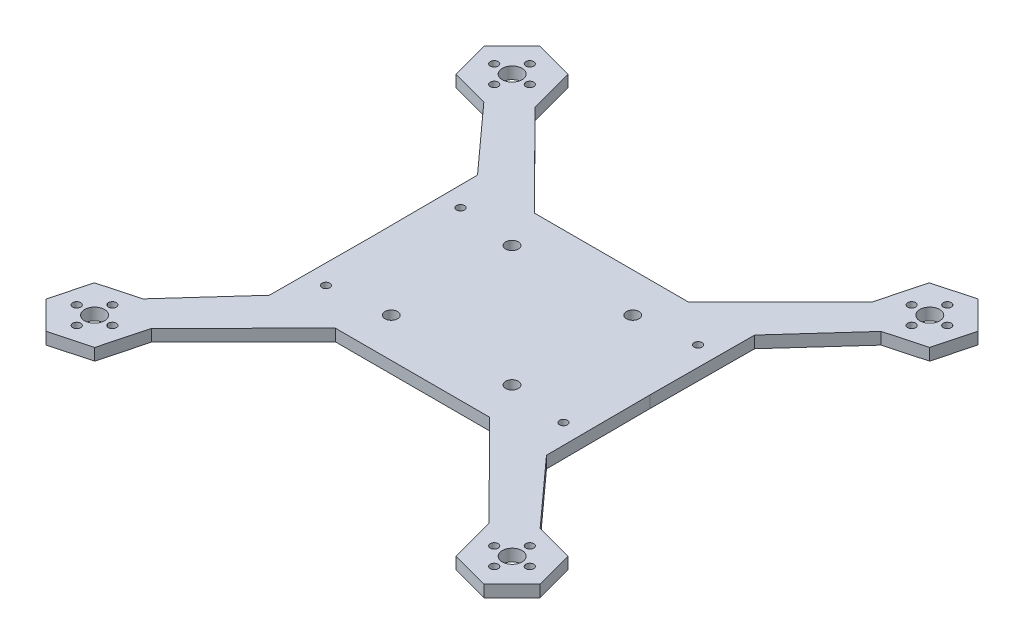
SolidWorks part; units mm, degrees
material "T700G"
ref_plane "Front Plane" through (0, 0, 0) normal (0, 0, 1) x (1, 0, 0)
ref_plane "Top Plane" through (0, 0, 0) normal (0, 1, 0) x (1, 0, 0)
ref_plane "Right Plane" through (0, 0, 0) normal (1, 0, 0) x (0, 0, -1)
sketch "Sketch1" plane through (0, 0, 0) normal (0, 1, 0) x (1, 0, 0)
  line L5 (-35, -35) -> (42.6186, 42.6186) construction
  line L6 (-35, 35) -> (35, -35) construction
  line L9 (0, 0) -> (42.4264, 42.4264) construction
  line L10 (52.7307, 48.2307) -> (52.7307, 57.2307) construction
  line L11 (30, 17) -> (30, 0) construction
  line L12 (0, 0) -> (0, 23.6863) construction
  line L28 (0, 0) -> (-174.2372, 0) construction
  line L41 (31.9599, 25.1581) -> (-25.1581, 25.1581) construction
  line L70 (42.6186, 48.4021) -> (19.4638, 25.1581)
  line L72 (48.2307, 52.7307) -> (57.2307, 52.7307) construction
  line L74 (48.2307, 52.7307) -> (52.7307, 48.2307) construction
  line L75 (55.3003, 62.3949) -> (45.646, 59.7881)
  line L77 (45.646, 59.7881) -> (42.6186, 48.4021)
  line L80 (50.185, 43.0729) -> (59.8153, 45.6732)
  line L83 (59.8153, 45.6732) -> (62.3849, 55.3374)
  line L85 (62.3849, 55.3374) -> (55.3003, 62.3949)
  line L87 (50.185, 43.0729) -> (35, 26.2883)
  line L88 (35, 26.2883) -> (34.873, 0)
  line L89 (34.873, -11.873) -> (34.873, 11.873) construction
  line L90 (-21.8355, 25.1581) -> (21.8355, 25.1581)
  line L94 (35, -26.2883) -> (34.873, 0)
  line L100 (48.2307, -52.7307) -> (52.7307, -48.2307) construction
  line L101 (48.2307, -52.7307) -> (57.2307, -52.7307) construction
  line L102 (52.7307, -48.2307) -> (52.7307, -57.2307) construction
  line L106 (62.3849, -55.3374) -> (55.3003, -62.3949)
  line L111 (59.8153, -45.6732) -> (62.3849, -55.3374)
  line L115 (50.185, -43.0729) -> (59.8153, -45.6732)
  line L116 (45.646, -59.7881) -> (42.6186, -48.4021)
  line L119 (55.3003, -62.3949) -> (45.646, -59.7881)
  line L127 (50.185, -43.0729) -> (35, -26.2883)
  line L128 (35, 26.2883) -> (34.873, 0)
  line L129 (35, -26.2883) -> (34.873, 0)
  line L135 (42.6186, -48.4021) -> (19.4638, -25.1581)
  line L138 (40.4517, 52.7386) -> (49.1512, 44.0725) [skipped]
  line L139 (-21.8355, -25.1581) -> (21.8355, -25.1581)
  line L140 (-48.2307, 52.7307) -> (-52.7307, 48.2307) construction
  line L141 (-48.2307, 52.7307) -> (-57.2307, 52.7307) construction
  line L142 (-52.7307, 48.2307) -> (-52.7307, 57.2307) construction
  line L143 (-62.3849, 55.3374) -> (-55.3003, 62.3949)
  line L144 (-59.8153, 45.6732) -> (-62.3849, 55.3374)
  line L145 (-50.185, 43.0729) -> (-59.8153, 45.6732)
  line L146 (-45.646, 59.7881) -> (-42.6186, 48.4021)
  line L147 (-55.3003, 62.3949) -> (-45.646, 59.7881)
  line L148 (-50.185, 43.0729) -> (-35, 26.2883)
  line L149 (-42.6186, 48.4021) -> (-19.4638, 25.1581)
  line L150 (-35, 26.2883) -> (-34.873, 0)
  line L151 (-35, -26.2883) -> (-34.873, 0)
  line L152 (-50.185, -43.0729) -> (-35, -26.2883)
  line L153 (-42.6186, -48.4021) -> (-19.4638, -25.1581)
  line L154 (-52.7307, -48.2307) -> (-52.7307, -57.2307) construction
  line L155 (-48.2307, -52.7307) -> (-57.2307, -52.7307) construction
  line L156 (-48.2307, -52.7307) -> (-52.7307, -48.2307) construction
  line L157 (-55.3003, -62.3949) -> (-45.646, -59.7881)
  line L158 (-45.646, -59.7881) -> (-42.6186, -48.4021)
  line L159 (-50.185, -43.0729) -> (-59.8153, -45.6732)
  line L160 (-59.8153, -45.6732) -> (-62.3849, -55.3374)
  line L161 (-62.3849, -55.3374) -> (-55.3003, -62.3949)
  circle A0 centre (-15.25, 15.25) radius 1.6
  circle A1 centre (15.25, 15.25) radius 1.6
  circle A2 centre (15.25, -15.25) radius 1.6
  circle A3 centre (-15.25, -15.25) radius 1.6
  circle A18 centre (30, 17) radius 1
  circle A19 centre (30, -17) radius 1
  circle A20 centre (-30, -17) radius 1
  circle A21 centre (-30, 17) radius 1
  circle A69 centre (52.7307, 52.7307) radius 8.6603 construction
  circle A70 centre (52.7307, 57.2307) radius 1
  circle A71 centre (52.7307, 48.2307) radius 1
  circle A72 centre (48.2307, 52.7307) radius 1
  circle A73 centre (57.2307, 52.7307) radius 1
  circle A124 centre (52.7307, -52.7307) radius 8.6603 construction
  circle A125 centre (57.2307, -52.7307) radius 1
  circle A126 centre (48.2307, -52.7307) radius 1
  circle A127 centre (52.7307, -48.2307) radius 1
  circle A128 centre (52.7307, -57.2307) radius 1
  circle A129 centre (-52.7307, 52.7307) radius 8.6603 construction
  circle A130 centre (-57.2307, 52.7307) radius 1
  circle A131 centre (-48.2307, 52.7307) radius 1
  circle A132 centre (-52.7307, 48.2307) radius 1
  circle A133 centre (-52.7307, 57.2307) radius 1
  circle A134 centre (-52.7307, -52.7307) radius 8.6603 construction
  circle A135 centre (-52.7307, -57.2307) radius 1
  circle A136 centre (-52.7307, -48.2307) radius 1
  circle A137 centre (-48.2307, -52.7307) radius 1
  circle A138 centre (-57.2307, -52.7307) radius 1
  point P0 (0, 0)
  point P8 (52.7307, 52.7307)
  point P9 (52.7307, 52.7307)
  point P17 (0, 0)
  point P45 (24.8566, 0)
  point P47 (30, 0)
  point P90 (0, 25.1581)
  point P95 (0, -25.1581)
  point P96 (0, 25.1581)
  point P99 (0, 25.1581)
  point P110 (0, -25.1581)
  point P118 (0, 0)
  point P126 (0, -25.1581)
  dimension "D3" = 3.2
  dimension "D16" = 2
  dimension "D1" = 70
  dimension "D2" = 4.5
  dimension "D4" = 30.5
  dimension "D6" = 4.5
  dimension "D7" = 20
  dimension "D15" = 17
  dimension "D12" = 30
  dimension "D5" = 4
  dimension "D17" = 2
extrude "Boss-Extrude1" add sketch "Sketch1" along normal blind 3
sketch "Sketch7" plane through (0, 3, 0) normal (0, 1, 0) x (1, 0, 0)
  line L0 (-57.2307, -52.7307) -> (-48.2307, -52.7307) construction
  line L1 (-52.7307, -57.2307) -> (-52.7307, -48.2307) construction
  line L2 (0, 0) -> (-75.1546, 0) construction
  line L3 (0, 0) -> (0, 55.538) construction
  circle A0 centre (-52.7307, -52.7307) radius 0.75
  circle A1 centre (-52.7307, 52.7307) radius 0.75
  circle A2 centre (52.7307, 52.7307) radius 0.75
  circle A3 centre (52.7307, -52.7307) radius 0.75
  dimension "D1" = 1.5
extrude "Boss-Extrude4" add sketch "Sketch7" along normal blind 0.05
sketch "Sketch8" plane through (0, 3, 0) normal (0, 1, 0) x (1, 0, 0)
  circle A0 centre (-52.7307, -52.7307) radius 2.5
  circle A1 centre (52.7693, -52.7307) radius 2.5
  circle A2 centre (52.7693, 52.7693) radius 2.5
  circle A3 centre (-52.7307, 52.7693) radius 2.5
  dimension "D1" = 2
  dimension "D2" = 2
extrude "Cut-Extrude7" cut sketch "Sketch8" against normal blind 10
